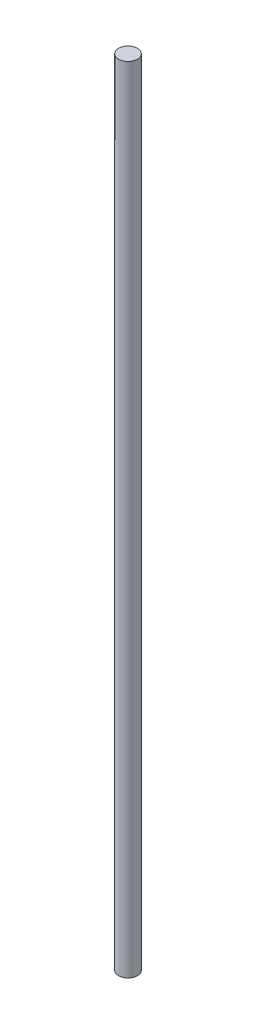
SolidWorks part; units mm, degrees
ref_plane "Plan de face" through (0, 0, 0) normal (0, 0, 1) x (1, 0, 0)
ref_plane "Plan de dessus" through (0, 0, 0) normal (0, 1, 0) x (1, 0, 0)
ref_plane "Plan de droite" through (0, 0, 0) normal (1, 0, 0) x (0, 0, -1)
sketch "Esquisse1" plane through (0, 0, 0) normal (0, 1, 0) x (1, 0, 0)
  circle A0 centre (0, 0) radius 2.5
  dimension "D1" = 5
extrude "Boss.-Extru.1" add sketch "Esquisse1" along normal blind 210
